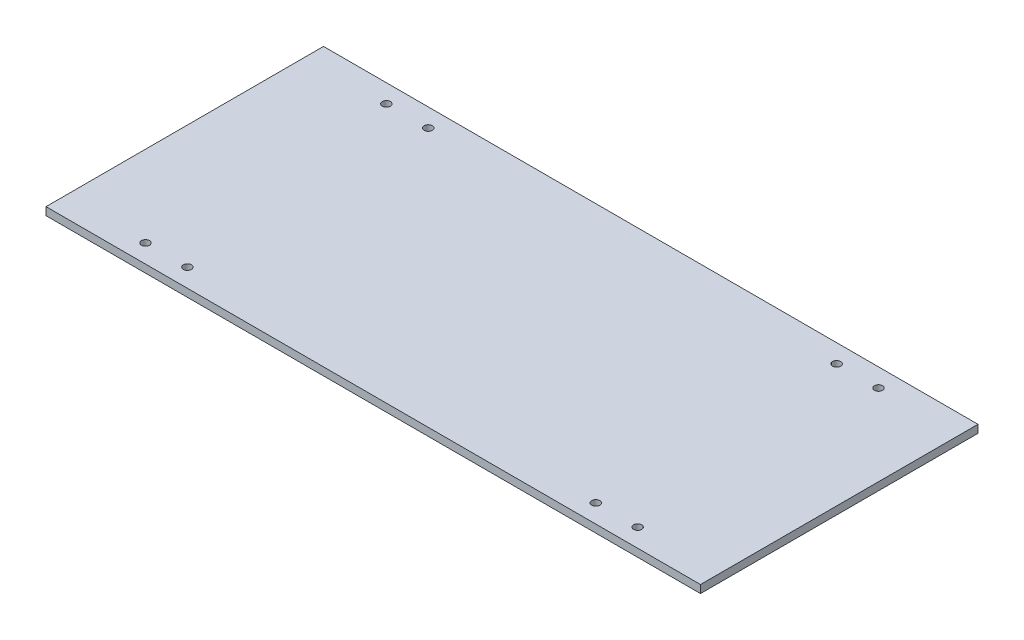
SolidWorks part; units mm, degrees
ref_plane "Front Plane" through (0, 0, 0) normal (0, 0, 1) x (1, 0, 0)
ref_plane "Top Plane" through (0, 0, 0) normal (0, 1, 0) x (1, 0, 0)
ref_plane "Right Plane" through (0, 0, 0) normal (1, 0, 0) x (0, 0, -1)
sketch "Sketch1" plane through (0, 0, 0) normal (0, 1, 0) x (1, 0, 0)
  line L0 (125, 106) -> (125, 0) construction
  line L1 (0, 106) -> (250, 106)
  line L2 (0, 106) -> (0, 0)
  line L3 (0, 0) -> (250, 0)
  line L4 (250, 106) -> (250, 0)
  line L5 (0, 53) -> (250, 53) construction
  circle A0 centre (31, 99) radius 1.55
  circle A1 centre (47, 99) radius 1.55
  circle A2 centre (203, 99) radius 1.55
  circle A3 centre (219, 99) radius 1.55
  circle A4 centre (219, 7) radius 1.55
  circle A5 centre (203, 7) radius 1.55
  circle A6 centre (47, 7) radius 1.55
  circle A7 centre (31, 7) radius 1.55
  dimension "D2" = 3.1
  dimension "D1" = 250
  dimension "D3" = 16
  dimension "D5" = 7
  dimension "D6" = 99
  dimension "D4" = 78
extrude "Boss-Extrude1" add sketch "Sketch1" along normal blind 3
equation "\"cf_tube_outer_diameter\"= 25mm"
equation "\"cf_tube_inner_diameter\" = 21mm"
equation "\"mid_plate_mid_to_top\" = 100mm"
equation "\"mid_plate_mid_to_bottom\" = 30mm"
equation "\"mid_plate_horizontal_spacing\"=250mm"
equation "\"cf_plate_thickness\" =4mm"
equation "\"mid_tube_length\" = 121mm"
equation "\"mid_support_plate_distance\" = 250mm"
equation "\"M3_hole_diameter\"= 3.1mm"
equation "\"﻿cf_tube_outer_diameter\"= 25mm"
equation "\"D2@Sketch1\"=\"M3_hole_diameter\""
